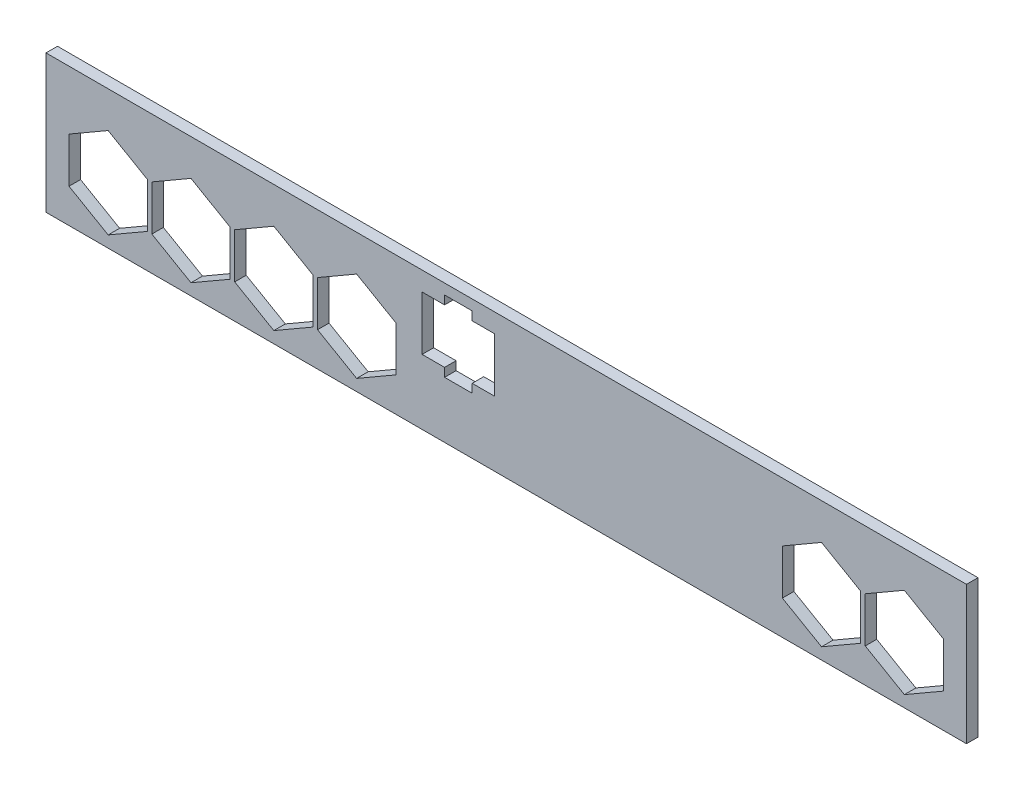
SolidWorks part; units mm, degrees
ref_plane "Front Plane" through (0, 0, 0) normal (0, 0, 1) x (1, 0, 0)
ref_plane "Top Plane" through (0, 0, 0) normal (0, 1, 0) x (1, 0, 0)
ref_plane "Right Plane" through (0, 0, 0) normal (1, 0, 0) x (0, 0, -1)
sketch "Sketch1" plane through (0, 0, 0) normal (0, 0, 1) x (1, 0, 0)
  line L1 (127, -19.05) -> (-127, -19.05)
  line L2 (127, -19.05) -> (127, 19.05)
  line L3 (127, 19.05) -> (-127, 19.05)
  line L4 (-127, -19.05) -> (-127, 19.05)
  line L5 (127, -19.05) -> (-127, 19.05) construction
  line L6 (127, 19.05) -> (-127, -19.05) construction
  point P0 (0, 0)
  dimension "D1" = 254
  dimension "D2" = 38.1
extrude "Boss-Extrude1" add sketch "Sketch1" along normal blind 3.175
sketch "Sketch2" plane through (0, 0, 3.175) normal (0, 0, 1) x (1, 0, 0)
  line L10 (-127, 19.05) -> (-127, -19.05) construction
  line L11 (-127, -19.05) -> (127, -19.05) construction
  line L12 (-13.208, 6.35) -> (-13.208, 16.1925) construction
  line L20 (-3.2068, -1.1113) -> (-3.2068, 13.8112)
  line L22 (-23.2093, -1.1113) -> (-23.2093, 13.8112)
  line L23 (-3.2068, -1.1113) -> (-23.2093, 13.8112) construction
  line L24 (-3.2068, 13.8112) -> (-23.2093, -1.1113) construction
  line L26 (-17.018, 13.8112) -> (-17.018, 16.1925)
  line L27 (-17.018, 16.1925) -> (-9.398, 16.1925)
  line L28 (-9.398, 13.8112) -> (-9.398, 16.1925)
  line L29 (-13.208, 6.35) -> (-3.2068, 6.35) construction
  line L30 (-9.398, -1.1113) -> (-9.398, -3.4925)
  line L31 (-17.018, -3.4925) -> (-9.398, -3.4925)
  line L32 (-17.018, -1.1113) -> (-17.018, -3.4925)
  line L34 (-9.398, -1.1113) -> (-3.2068, -1.1113)
  line L35 (-17.018, -1.1113) -> (-23.2093, -1.1113)
  line L36 (-9.398, 13.8112) -> (-3.2068, 13.8112)
  line L37 (-17.018, 13.8112) -> (-23.2093, 13.8112)
  point P0 (-13.208, 6.35)
  point P5 (-13.208, 6.35)
  point P14 (-13.208, 6.35)
  point P25 (-13.208, 16.1925)
  dimension "D1" = 14.9225
  dimension "D2" = 20.0025
  dimension "D4" = 113.792
  dimension "D5" = 25.4
  dimension "D3" = 19.685
  dimension "D8" = 7.62
sketch "Sketch3" plane through (0, 0, 3.175) normal (0, 0, 1) x (1, 0, 0)
  line L0 (0, 19.05) -> (0, -16.8073) construction
  line L1 (127, 19.05) -> (-127, 19.05) construction
  line L2 (-50.8, 19.05) -> (-50.8, -16.8073) construction
  line L3 (-101.6, 19.05) -> (-101.6, -16.8073) construction
  line L4 (50.8, 19.05) -> (50.8, -16.8073) construction
  line L5 (101.6, 19.05) -> (101.6, -16.8073) construction
  dimension "D1" = 3
  dimension "D2" = 3
sketch "Sketch4" plane through (0, 0, 3.175) normal (0, 0, 1) x (1, 0, 0)
  line L1 (-118.11, 9.0548) -> (-33.02, 9.0548) construction
  line L2 (-120.65, 6.5148) -> (-120.65, -13.335) construction
  line L3 (-118.11, -15.875) -> (-33.02, -15.875) construction
  line L4 (-30.48, 6.5148) -> (-30.48, -13.335) construction
  line L5 (-118.11, 12.2298) -> (-33.02, 12.2298) construction
  line L6 (-27.305, 6.5148) -> (-27.305, -13.335) construction
  line L7 (-118.11, -19.05) -> (-33.02, -19.05) construction
  line L8 (-123.825, 6.5148) -> (-123.825, -13.335) construction
  line L10 (-127, -19.05) -> (127, -19.05) construction
  line L11 (-127, 19.05) -> (-127, -19.05) construction
  line L13 (-99.0601, -9.6425) -> (-99.0601, 2.8224)
  line L14 (-99.0601, 2.8224) -> (-109.8551, 9.0548)
  line L15 (-109.8551, 9.0548) -> (-120.65, 2.8224)
  line L16 (-120.65, 2.8224) -> (-120.65, -9.6425)
  line L17 (-120.65, -9.6425) -> (-109.8551, -15.875)
  line L18 (-109.8551, -15.875) -> (-99.0601, -9.6425)
  line L19 (-76.2001, -9.6425) -> (-76.2001, 2.8224)
  line L20 (-76.2001, 2.8224) -> (-86.9951, 9.0548)
  line L21 (-86.9951, 9.0548) -> (-97.79, 2.8224)
  line L22 (-97.79, 2.8224) -> (-97.79, -9.6425)
  line L23 (-97.79, -9.6425) -> (-86.9951, -15.875)
  line L24 (-86.9951, -15.875) -> (-76.2001, -9.6425)
  line L25 (-53.3401, -9.6425) -> (-53.3401, 2.8224)
  line L26 (-53.3401, 2.8224) -> (-64.1351, 9.0548)
  line L27 (-64.1351, 9.0548) -> (-74.93, 2.8224)
  line L28 (-74.93, 2.8224) -> (-74.93, -9.6425)
  line L29 (-74.93, -9.6425) -> (-64.1351, -15.875)
  line L30 (-64.1351, -15.875) -> (-53.3401, -9.6425)
  line L31 (-30.4801, -9.6425) -> (-30.4801, 2.8224)
  line L32 (-30.4801, 2.8224) -> (-41.2751, 9.0548)
  line L33 (-41.2751, 9.0548) -> (-52.07, 2.8224)
  line L34 (-52.07, 2.8224) -> (-52.07, -9.6425)
  line L35 (-52.07, -9.6425) -> (-41.2751, -15.875)
  line L36 (-41.2751, -15.875) -> (-30.4801, -9.6425)
  line L44 (127, -19.05) -> (127, 19.05) construction
  line L45 (120.65, -9.6425) -> (120.65, 2.8224)
  line L46 (120.65, 2.8224) -> (109.8551, 9.0548)
  line L47 (109.8551, 9.0548) -> (99.0601, 2.8224)
  line L48 (99.0601, 2.8224) -> (99.0601, -9.6425)
  line L49 (99.0601, -9.6425) -> (109.8551, -15.875)
  line L50 (109.8551, -15.875) -> (120.65, -9.6425)
  line L51 (97.79, -9.6425) -> (97.79, 2.8224)
  line L52 (97.79, 2.8224) -> (86.9951, 9.0548)
  line L53 (86.9951, 9.0548) -> (76.2001, 2.8224)
  line L54 (76.2001, 2.8224) -> (76.2001, -9.6425)
  line L55 (76.2001, -9.6425) -> (86.9951, -15.875)
  line L56 (86.9951, -15.875) -> (97.79, -9.6425)
  arc A0 (-120.65, -13.335) -> (-118.11, -15.875) centre (-118.11, -13.335) ccw construction
  arc A1 (-30.48, -13.335) -> (-33.02, -15.875) centre (-33.02, -13.335) cw construction
  arc A2 (-30.48, 6.5148) -> (-33.02, 9.0548) centre (-33.02, 6.5148) ccw construction
  arc A3 (-120.65, 6.5148) -> (-118.11, 9.0548) centre (-118.11, 6.5148) cw construction
  arc A4 (-27.305, 6.5148) -> (-33.02, 12.2298) centre (-33.02, 6.5148) ccw construction
  arc A5 (-27.305, -13.335) -> (-33.02, -19.05) centre (-33.02, -13.335) cw construction
  arc A6 (-123.825, -13.335) -> (-118.11, -19.05) centre (-118.11, -13.335) ccw construction
  arc A7 (-123.825, 6.5148) -> (-118.11, 12.2298) centre (-118.11, 6.5148) cw construction
  circle A8 centre (-109.8551, -3.4101) radius 10.7949 construction
  circle A9 centre (-109.8551, -3.4101) radius 12.4649 construction
  circle A10 centre (109.8551, -3.4101) radius 10.7949 construction
  point P67 (127, 0)
  dimension "D1" = 90.17
  dimension "D4" = 2.54
  dimension "D5" = 3.175
  dimension "D6" = 3.175
  dimension "D3" = 2.54
  dimension "D2" = 24.9298
  dimension "D8" = 22.86
  dimension "D9" = 6.35
  dimension "D11" = 22.86
  dimension "D7" = 4
  dimension "D10" = 2
extrude "Cut-Extrude1" cut sketch "Sketch4" against normal blind 10.414
extrude "Cut-Extrude2" cut sketch "Sketch2" against normal blind 3.175
ref_plane "Plane1" through (86.9951, 0, 0) normal (1, 0, 0) x (0, 0, -1)
